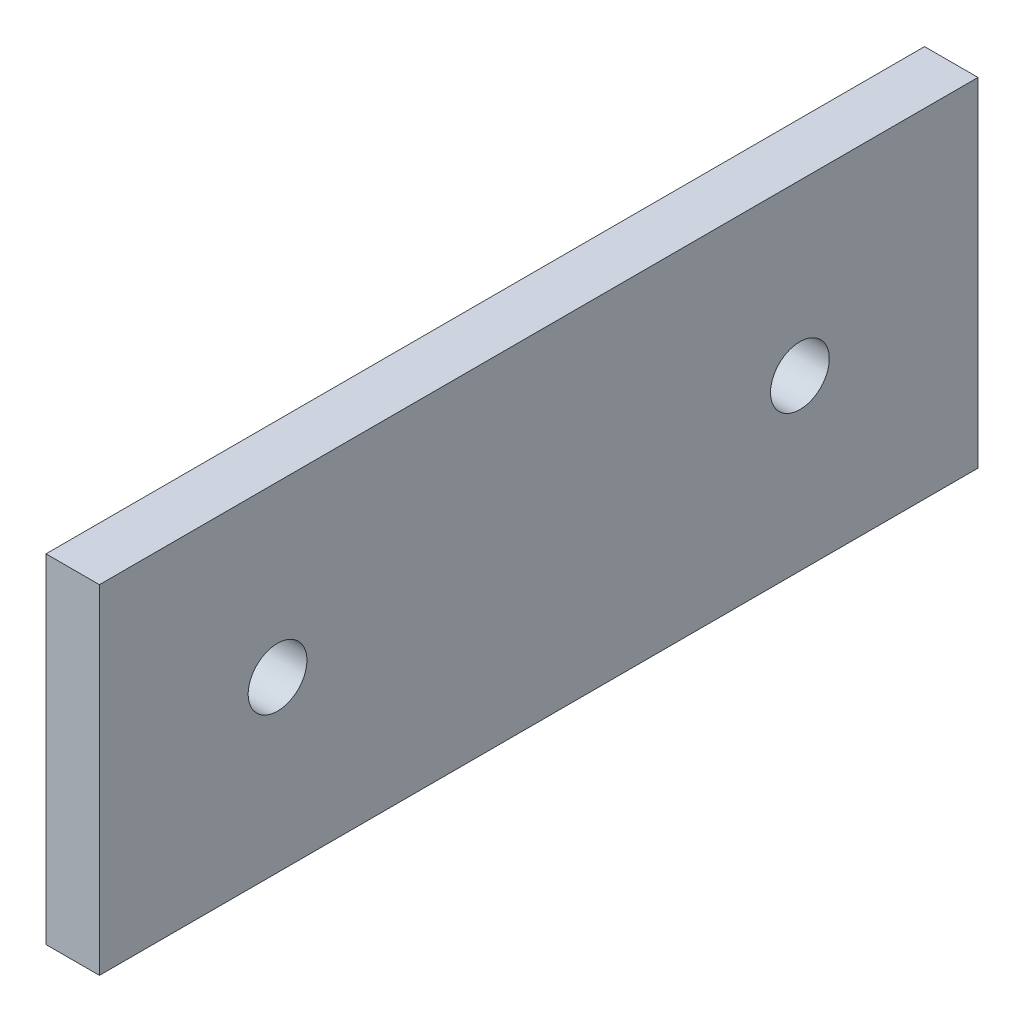
SolidWorks part; units mm, degrees
ref_plane "前视基准面" through (0, 0, 0) normal (0, 0, 1) x (1, 0, 0)
ref_plane "上视基准面" through (0, 0, 0) normal (0, 1, 0) x (1, 0, 0)
ref_plane "右视基准面" through (0, 0, 0) normal (1, 0, 0) x (0, 0, -1)
sketch "草图1" plane through (0, 0, 0) normal (0, 0, 1) x (1, 0, 0)
  line L1 (0, 0) -> (13, 0)
  line L2 (0, 0) -> (0, 13)
  line L3 (0, 13) -> (13, 13)
  line L4 (13, 0) -> (13, 13)
  dimension "D1" = 13
  dimension "D2" = 13
extrude "拉伸-薄壁1" add sketch "草图1" along normal blind 49.33 thin
sketch "草图2" plane through (-3, 0, 0) normal (-1, 0, 0) x (0, 0, 1)
  line L0 (0, 16) -> (0, -3) construction
  line L1 (49.33, 16) -> (49.33, -3) construction
  circle A0 centre (10, 6.5) radius 1.65
  circle A1 centre (39.33, 6.5) radius 1.65
  dimension "D1" = 3.3
  dimension "D2" = 3.3
  dimension "D3" = 10
  dimension "D4" = 10
extrude "切除-拉伸1" cut sketch "草图2" against normal blind 30
sketch "草图3" plane through (16, 0, 0) normal (1, 0, 0) x (0, 0, -1)
  line L1 (-49.33, 16) -> (0, 16)
  line L2 (-49.33, 16) -> (-49.33, -3)
  line L3 (-49.33, -3) -> (0, -3)
  line L4 (0, 16) -> (0, -3)
extrude "切除-拉伸2" cut sketch "草图3" against normal blind 16
sketch "草图4" plane through (0, 0, 0) normal (1, 0, 0) x (0, 0, -1)
  line L0 (0, 16) -> (0, -3) construction
  line L1 (-28.33, 12.85) -> (-21, 12.85)
  line L2 (-28.33, 12.85) -> (-28.33, 0.15)
  line L3 (-28.33, 0.15) -> (-21, 0.15)
  line L4 (-21, 12.85) -> (-21, 0.15)
  line L5 (-49.33, 16) -> (-49.33, -3) construction
  line L6 (-49.33, -3) -> (0, -3) construction
  line L7 (0, 16) -> (-49.33, 16) construction
  point P8 (-21, 6.5)
  dimension "D1" = 21
  dimension "D2" = 21
  dimension "D3" = 12.7
  dimension "D4" = 9.5
  dimension "D5" = 3.15
  dimension "D6" = 3.15
extrude "凸台-拉伸1" [suppressed] add sketch "草图4" along normal blind 2.9
chamfer "倒角1" [suppressed] distance 2.5 angle 45
